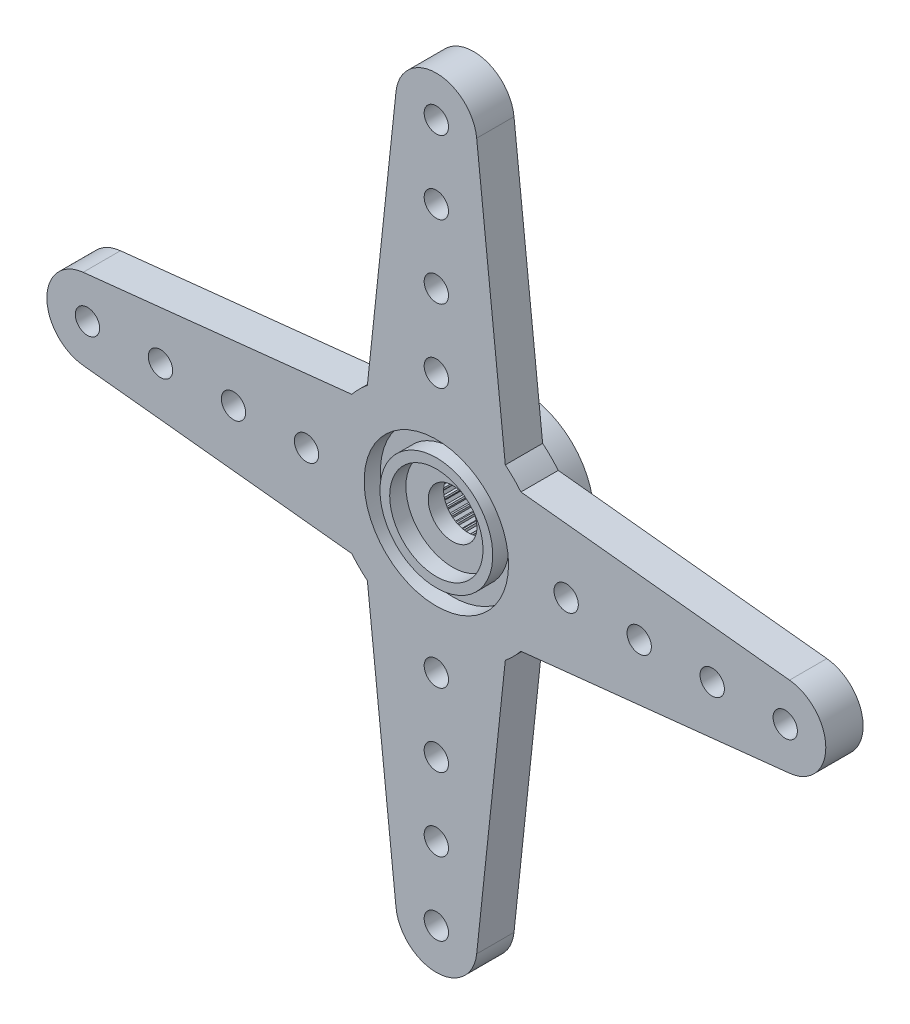
SolidWorks part; units mm, degrees
ref_plane "Plan de face" through (0, 0, 0) normal (0, 0, 1) x (1, 0, 0)
ref_plane "Plan de dessus" through (0, 0, 0) normal (0, 1, 0) x (1, 0, 0)
ref_plane "Plan de droite" through (0, 0, 0) normal (1, 0, 0) x (0, 0, -1)
sketch "Esquisse1" plane through (0, 0, 0) normal (0, 0, 1) x (1, 0, 0)
  line L0 (-21.5, 0) -> (0, 0) construction
  line L1 (-5.2118, 4.25) -> (-5.2118, -4.25) construction
  line L2 (-21.7649, 2.4859) -> (-5.2118, 4.25)
  line L3 (-21.7649, -2.4859) -> (-5.2118, -4.25)
  line L4 (0, 0) -> (0, 6.725) construction
  line L5 (21.7649, -2.4859) -> (5.2118, -4.25)
  line L6 (21.7649, 2.4859) -> (5.2118, 4.25)
  line L7 (2.4859, 21.7649) -> (4.25, 5.2118)
  line L8 (-2.4859, 21.7649) -> (-4.25, 5.2118)
  line L9 (-2.4859, -21.7649) -> (-4.25, -5.2118)
  line L10 (2.4859, -21.7649) -> (4.25, -5.2118)
  line L11 (0, 0) -> (5.2118, 4.25) construction
  line L12 (0, 0) -> (4.25, -5.2118) construction
  arc A0 (-5.2118, -4.25) -> (-4.25, -5.2118) centre (0, 0) ccw
  arc A3 (-21.7649, 2.4859) -> (-21.7649, -2.4859) centre (-21.5, 0) ccw
  arc A4 (21.7649, 2.4859) -> (21.7649, -2.4859) centre (21.5, 0) cw
  arc A5 (5.2118, 4.25) -> (4.25, 5.2118) centre (0, 0) ccw
  arc A6 (2.4859, 21.7649) -> (-2.4859, 21.7649) centre (0, 21.5) ccw
  arc A7 (2.4859, -21.7649) -> (-2.4859, -21.7649) centre (0, -21.5) cw
  arc A8 (-4.25, 5.2118) -> (-5.2118, 4.25) centre (0, 0) ccw
  arc A9 (4.25, -5.2118) -> (5.2118, -4.25) centre (0, 0) ccw
  dimension "D1" = 13.45
  dimension "D2" = 2.5
  dimension "D4" = 2
  dimension "D3" = 43
  dimension "D5" = 8.5
  dimension "D6" = 90
extrude "Boss.-Extru.1" add sketch "Esquisse1" along normal blind 2.3
sketch "Esquisse2" plane through (0, 0, 2.3) normal (0, 0, 1) x (1, 0, 0)
  circle A0 centre (0, 0) radius 4.45
  dimension "D1" = 8.9
extrude "Enlèv. mat.-Extru.1" cut sketch "Esquisse2" against normal blind 1
sketch "Esquisse3" plane through (0, 0, 1.3) normal (0, 0, 1) x (1, 0, 0)
  circle A0 centre (0, 0) radius 2.875
  circle A1 centre (0, 0) radius 3.475
  dimension "D1" = 5.75
  dimension "D2" = 0.6
extrude "Boss.-Extru.2" add sketch "Esquisse3" along normal up to surface (1 mm away) up to face at (4.45, 0, 2.3)
sketch "Esquisse4" plane through (0, 0, 0) normal (0, 0, -1) x (-1, 0, 0)
  circle A0 centre (0, 0) radius 4.4
  dimension "D1" = 8.8
extrude "Boss.-Extru.3" add sketch "Esquisse4" along normal blind 3
sketch "Esquisse5" plane through (0, 0, 1.3) normal (0, 0, 1) x (1, 0, 0)
  circle A0 centre (0, 0) radius 1.5
  dimension "D1" = 3
extrude "Enlèv. mat.-Extru.2" cut sketch "Esquisse5" against normal through all
sketch "Esquisse6" plane through (0, 0, -3) normal (0, 0, -1) x (-1, 0, 0)
  line L0 (-0.1143, 2.9978) -> (-0.0406, 2.8652)
  line L1 (0.0406, 2.8652) -> (0.1143, 2.9978)
  line L2 (0, 2.8652) -> (0, 0) construction
  line L3 (-0.0406, 2.8652) -> (0.0406, 2.8652)
  line L4 (0.439, 2.8316) -> (0.5304, 2.9527)
  line L5 (0.3041, 2.9846) -> (0.3585, 2.8429)
  line L6 (0.3585, 2.8429) -> (0.439, 2.8316)
  line L7 (0.8288, 2.743) -> (0.9362, 2.8502)
  line L8 (0.7165, 2.9132) -> (0.7507, 2.7654)
  line L9 (0.7507, 2.7654) -> (0.8288, 2.743)
  line L10 (1.2025, 2.6009) -> (1.3237, 2.6922)
  line L11 (1.1149, 2.7851) -> (1.1283, 2.634)
  line L12 (1.1283, 2.634) -> (1.2025, 2.6009)
  line L13 (1.5527, 2.4083) -> (1.6855, 2.4817)
  line L14 (1.4917, 2.6029) -> (1.4839, 2.4513)
  line L15 (1.4839, 2.4513) -> (1.5527, 2.4083)
  line L16 (1.8728, 2.1687) -> (2.0145, 2.223)
  line L17 (1.8394, 2.3699) -> (1.8106, 2.2209)
  line L18 (1.8106, 2.2209) -> (1.8728, 2.1687)
  line L19 (2.1564, 1.887) -> (2.3043, 1.921)
  line L20 (2.1514, 2.0909) -> (2.1021, 1.9473)
  line L21 (2.1021, 1.9473) -> (2.1564, 1.887)
  line L22 (2.398, 1.5685) -> (2.5492, 1.5816)
  line L23 (2.4214, 1.7711) -> (2.3526, 1.6358)
  line L24 (2.3526, 1.6358) -> (2.398, 1.5685)
  line L25 (2.593, 1.2195) -> (2.7445, 1.2114)
  line L26 (2.6443, 1.4169) -> (2.5574, 1.2925)
  line L27 (2.5574, 1.2925) -> (2.593, 1.2195)
  line L28 (2.7375, 0.8468) -> (2.8864, 0.8177)
  line L29 (2.8158, 1.0351) -> (2.7124, 0.924)
  line L30 (2.7124, 0.924) -> (2.7375, 0.8468)
  line L31 (2.8287, 0.4575) -> (2.9721, 0.408)
  line L32 (2.9324, 0.6331) -> (2.8146, 0.5375)
  line L33 (2.8146, 0.5375) -> (2.8287, 0.4575)
  line L34 (2.8648, 0.0594) -> (3, -0.0096)
  line L35 (2.992, 0.2188) -> (2.862, 0.1406)
  line L36 (2.862, 0.1406) -> (2.8648, 0.0594)
  line L37 (2.8452, -0.3399) -> (2.9695, -0.427)
  line L38 (2.9933, -0.1997) -> (2.8537, -0.2591)
  line L39 (2.8537, -0.2591) -> (2.8452, -0.3399)
  line L40 (2.7702, -0.7325) -> (2.8811, -0.8361)
  line L41 (2.9364, -0.6144) -> (2.7899, -0.6537)
  line L42 (2.7899, -0.6537) -> (2.7702, -0.7325)
  line L43 (2.6413, -1.111) -> (2.7367, -1.229)
  line L44 (2.8223, -1.017) -> (2.6717, -1.0357)
  line L45 (2.6717, -1.0357) -> (2.6413, -1.111)
  line L46 (2.461, -1.4677) -> (2.5391, -1.5979)
  line L47 (2.6533, -1.3999) -> (2.5016, -1.3974)
  line L48 (2.5016, -1.3974) -> (2.461, -1.4677)
  line L49 (2.2328, -1.796) -> (2.292, -1.9357)
  line L50 (2.4327, -1.7556) -> (2.2828, -1.732)
  line L51 (2.2828, -1.732) -> (2.2328, -1.796)
  line L52 (1.9611, -2.0892) -> (2.0003, -2.2358)
  line L53 (2.1647, -2.0771) -> (2.0195, -2.0328)
  line L54 (2.0195, -2.0328) -> (1.9611, -2.0892)
  line L55 (1.6512, -2.3418) -> (1.6696, -2.4925)
  line L56 (1.8545, -2.3581) -> (1.7169, -2.2941)
  line L57 (1.7169, -2.2941) -> (1.6512, -2.3418)
  line L58 (1.3093, -2.5488) -> (1.3065, -2.7006)
  line L59 (1.5083, -2.5933) -> (1.381, -2.5107)
  line L60 (1.381, -2.5107) -> (1.3093, -2.5488)
  line L61 (0.9418, -2.7063) -> (0.9179, -2.8561)
  line L62 (1.1327, -2.7779) -> (1.0181, -2.6785)
  line L63 (1.0181, -2.6785) -> (0.9418, -2.7063)
  line L64 (0.556, -2.811) -> (0.5115, -2.9561)
  line L65 (0.7351, -2.9086) -> (0.6354, -2.7941)
  line L66 (0.6354, -2.7941) -> (0.556, -2.811)
  line L67 (0.1594, -2.861) -> (0.0951, -2.9985)
  line L68 (0.3231, -2.9825) -> (0.2404, -2.8553)
  line L69 (0.2404, -2.8553) -> (0.1594, -2.861)
  line L70 (-0.2404, -2.8553) -> (-0.3231, -2.9825)
  line L71 (-0.0951, -2.9985) -> (-0.1594, -2.861)
  line L72 (-0.1594, -2.861) -> (-0.2404, -2.8553)
  line L73 (-0.6354, -2.7941) -> (-0.7351, -2.9086)
  line L74 (-0.5115, -2.9561) -> (-0.556, -2.811)
  line L75 (-0.556, -2.811) -> (-0.6354, -2.7941)
  line L76 (-1.0181, -2.6785) -> (-1.1327, -2.7779)
  line L77 (-0.9179, -2.8561) -> (-0.9418, -2.7063)
  line L78 (-0.9418, -2.7063) -> (-1.0181, -2.6785)
  line L79 (-1.381, -2.5107) -> (-1.5083, -2.5933)
  line L80 (-1.3065, -2.7006) -> (-1.3093, -2.5488)
  line L81 (-1.3093, -2.5488) -> (-1.381, -2.5107)
  line L82 (-1.7169, -2.2941) -> (-1.8545, -2.3581)
  line L83 (-1.6696, -2.4925) -> (-1.6512, -2.3418)
  line L84 (-1.6512, -2.3418) -> (-1.7169, -2.2941)
  line L85 (-2.0195, -2.0328) -> (-2.1647, -2.0771)
  line L86 (-2.0003, -2.2358) -> (-1.9611, -2.0892)
  line L87 (-1.9611, -2.0892) -> (-2.0195, -2.0328)
  line L88 (-2.2828, -1.732) -> (-2.4327, -1.7556)
  line L89 (-2.292, -1.9357) -> (-2.2328, -1.796)
  line L90 (-2.2328, -1.796) -> (-2.2828, -1.732)
  line L91 (-2.5016, -1.3974) -> (-2.6533, -1.3999)
  line L92 (-2.5391, -1.5979) -> (-2.461, -1.4677)
  line L93 (-2.461, -1.4677) -> (-2.5016, -1.3974)
  line L94 (-2.6717, -1.0357) -> (-2.8223, -1.017)
  line L95 (-2.7367, -1.229) -> (-2.6413, -1.111)
  line L96 (-2.6413, -1.111) -> (-2.6717, -1.0357)
  line L97 (-2.7899, -0.6537) -> (-2.9364, -0.6144)
  line L98 (-2.8811, -0.8361) -> (-2.7702, -0.7325)
  line L99 (-2.7702, -0.7325) -> (-2.7899, -0.6537)
  line L100 (-2.8537, -0.2591) -> (-2.9933, -0.1997)
  line L101 (-2.9695, -0.427) -> (-2.8452, -0.3399)
  line L102 (-2.8452, -0.3399) -> (-2.8537, -0.2591)
  line L103 (-2.862, 0.1406) -> (-2.992, 0.2188)
  line L104 (-3, -0.0096) -> (-2.8648, 0.0594)
  line L105 (-2.8648, 0.0594) -> (-2.862, 0.1406)
  line L106 (-2.8146, 0.5375) -> (-2.9324, 0.6331)
  line L107 (-2.9721, 0.408) -> (-2.8287, 0.4575)
  line L108 (-2.8287, 0.4575) -> (-2.8146, 0.5375)
  line L109 (-2.7124, 0.924) -> (-2.8158, 1.0351)
  line L110 (-2.8864, 0.8177) -> (-2.7375, 0.8468)
  line L111 (-2.7375, 0.8468) -> (-2.7124, 0.924)
  line L112 (-2.5574, 1.2925) -> (-2.6443, 1.4169)
  line L113 (-2.7445, 1.2114) -> (-2.593, 1.2195)
  line L114 (-2.593, 1.2195) -> (-2.5574, 1.2925)
  line L115 (-2.3526, 1.6358) -> (-2.4214, 1.7711)
  line L116 (-2.5492, 1.5816) -> (-2.398, 1.5685)
  line L117 (-2.398, 1.5685) -> (-2.3526, 1.6358)
  line L118 (-2.1021, 1.9473) -> (-2.1514, 2.0909)
  line L119 (-2.3043, 1.921) -> (-2.1564, 1.887)
  line L120 (-2.1564, 1.887) -> (-2.1021, 1.9473)
  line L121 (-1.8106, 2.2209) -> (-1.8394, 2.3699)
  line L122 (-2.0145, 2.223) -> (-1.8728, 2.1687)
  line L123 (-1.8728, 2.1687) -> (-1.8106, 2.2209)
  line L124 (-1.4839, 2.4513) -> (-1.4917, 2.6029)
  line L125 (-1.6855, 2.4817) -> (-1.5527, 2.4083)
  line L126 (-1.5527, 2.4083) -> (-1.4839, 2.4513)
  line L127 (-1.1283, 2.634) -> (-1.1149, 2.7851)
  line L128 (-1.3237, 2.6922) -> (-1.2025, 2.6009)
  line L129 (-1.2025, 2.6009) -> (-1.1283, 2.634)
  line L130 (-0.7507, 2.7654) -> (-0.7165, 2.9132)
  line L131 (-0.9362, 2.8502) -> (-0.8288, 2.743)
  line L132 (-0.8288, 2.743) -> (-0.7507, 2.7654)
  line L133 (-0.3585, 2.8429) -> (-0.3041, 2.9846)
  line L134 (-0.5304, 2.9527) -> (-0.439, 2.8316)
  line L135 (-0.439, 2.8316) -> (-0.3585, 2.8429)
  circle A0 centre (0, 0) radius 3
  point P187 (0, 0)
  dimension "D1" = 6
  dimension "D2" = 45
extrude "Enlèv. mat.-Extru.3" cut sketch "Esquisse6" against normal blind 3.35
sketch "Esquisse7" plane through (0, 0, 2.3) normal (0, 0, 1) x (1, 0, 0)
  line L0 (0, 0) -> (-8, 0) construction
  line L1 (0, 0) -> (0, 8) construction
  line L2 (0, -2.915) -> (0, 2.915) construction
  circle A0 centre (-21.5, 0) radius 0.75
  circle A5 centre (0, 21.5) radius 0.75
  circle A6 centre (0, 17) radius 0.75
  circle A7 centre (-17, 0) radius 0.75
  circle A8 centre (-12.5, 0) radius 0.75
  circle A9 centre (-8, 0) radius 0.75
  circle A10 centre (8, 0) radius 0.75
  circle A11 centre (12.5, 0) radius 0.75
  circle A12 centre (17, 0) radius 0.75
  circle A13 centre (21.5, 0) radius 0.75
  circle A14 centre (0, 12.5) radius 0.75
  circle A15 centre (0, 8) radius 0.75
  circle A16 centre (0, -8) radius 0.75
  circle A17 centre (0, -12.5) radius 0.75
  circle A18 centre (0, -17) radius 0.75
  circle A19 centre (0, -21.5) radius 0.75
  dimension "D1" = 1.5
  dimension "D2" = 4
  dimension "D3" = 2
  dimension "D4" = 90
extrude "Enlèv. mat.-Extru.4" cut sketch "Esquisse7" against normal blind 3.35
